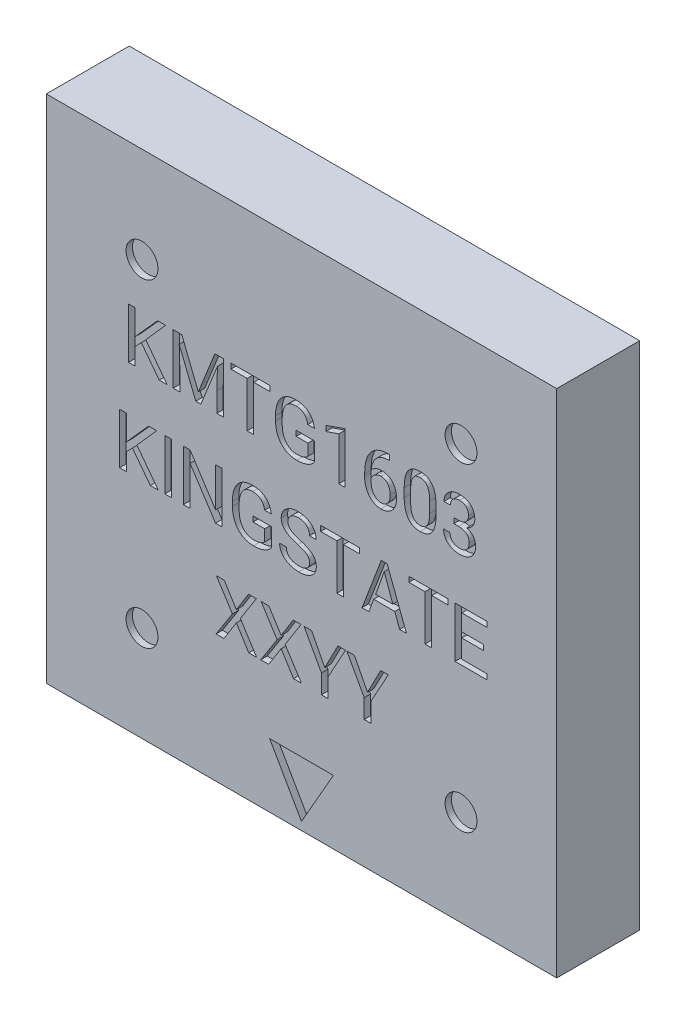
SolidWorks part; units mm, degrees
ref_plane "Plan de face" through (0, 0, 0) normal (0, 0, 1) x (1, 0, 0)
ref_plane "Plan de dessus" through (0, 0, 0) normal (0, 1, 0) x (1, 0, 0)
ref_plane "Plan de droite" through (0, 0, 0) normal (1, 0, 0) x (0, 0, -1)
sketch "Esquisse1" plane through (0, 0, 0) normal (0, 0, 1) x (1, 0, 0)
  line L1 (0, 0) -> (16, 0)
  line L2 (0, 0) -> (0, -16)
  line L3 (0, -16) -> (16, -16)
  line L4 (16, 0) -> (16, -16)
  dimension "D1" = 16
  dimension "D2" = 16
extrude "Boss.-Extru.1" add sketch "Esquisse1" along normal blind 2.6
sketch "Esquisse2" plane through (0, 0, 2.6) normal (0, 0, 1) x (1, 0, 0)
  line L0 (16, 0) -> (0, 0) construction
  line L1 (0, 0) -> (0, -16) construction
  line L2 (16, -16) -> (16, 0) construction
  line L3 (0, -16) -> (16, -16) construction
  line L4 (6.9992, -14) -> (7.9992, -15.75)
  line L5 (7.9992, -15.75) -> (8.9992, -14)
  line L6 (8.9992, -14) -> (6.9992, -14)
  line L8 (0, -6) -> (16, -6)
  line L9 (0, -9) -> (16, -9)
  line L10 (0, -12) -> (16, -12)
  circle A0 centre (3, -3) radius 0.5
  circle A1 centre (13, -3) radius 0.5
  circle A2 centre (3, -13) radius 0.5
  circle A3 centre (13, -13) radius 0.5
  text T0 "KMTG1603" font "Century Gothic" height in points 6
  text T1 "KINGSTATE" font "Century Gothic" height in points 6
  text T2 "XXYY" font "Century Gothic" height in points 6
  dimension "D2" = 1
  dimension "D4" = 1
  dimension "D5" = 1
  dimension "D6" = 1
  dimension "D1" = 3
  dimension "D3" = 3
  dimension "D7" = 3
  dimension "D8" = 3
  dimension "D9" = 3
  dimension "D10" = 3
  dimension "D11" = 3
  dimension "D12" = 3
  dimension "D13" = 2
  dimension "D14" = 1
  dimension "D15" = 1
  dimension "D16" = 7.9992
  dimension "D17" = 0.25
  dimension "D18" = 6
  dimension "D19" = 3
  dimension "D20" = 3
extrude "Enlèv. mat.-Extru.1" cut sketch "Esquisse2" against normal blind 0.2 contours A0 | A1 | A3 | A2 | L5 L6 L4
sketch "Esquisse3" plane through (0, 0, 2.6) normal (0, 0, 1) x (1, 0, 0)
  text T0 "KINGSTATE" font "Roboto" height in points 6
  text T1 "KMTG1603" font "Roboto" height in points 6
  text T2 "XXYY" font "Roboto" height in points 6
extrude "Enlèv. mat.-Extru.2" cut sketch "Esquisse3" against normal blind 0.2
